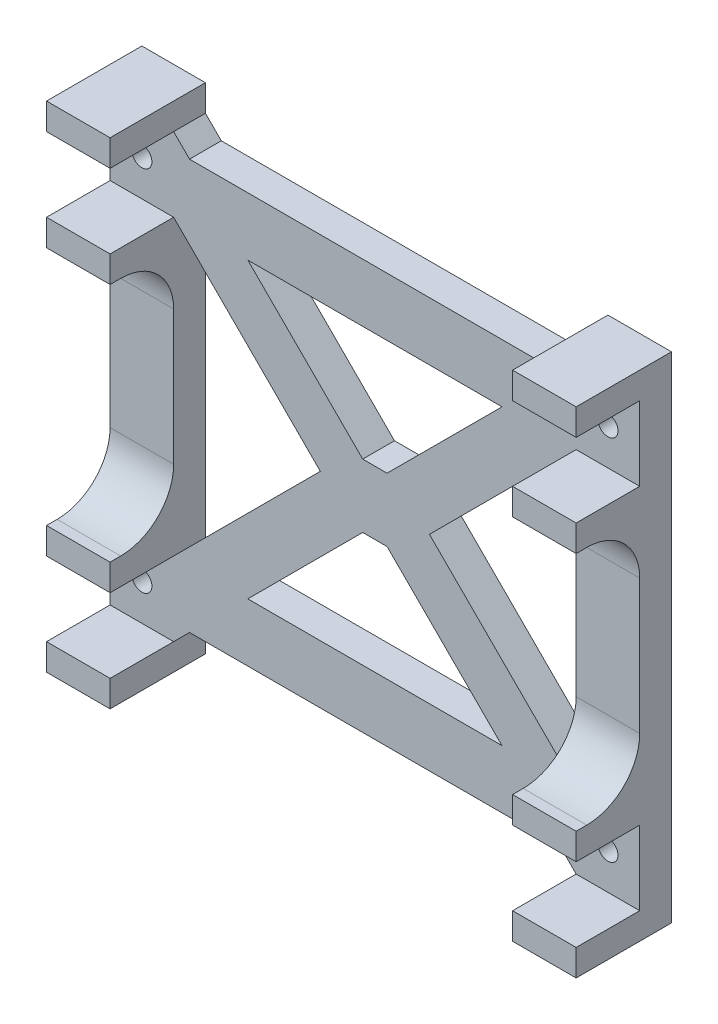
SolidWorks part; units mm, degrees
ref_plane "Plan de face" through (0, 0, 0) normal (0, 0, 1) x (1, 0, 0)
ref_plane "Plan de dessus" through (0, 0, 0) normal (0, 1, 0) x (1, 0, 0)
ref_plane "Plan de droite" through (0, 0, 0) normal (1, 0, 0) x (0, 0, -1)
sketch "Esquisse1" plane through (0, 0, 0) normal (0, 0, 1) x (1, 0, 0)
  line L1 (-3, -4) -> (3, -4)
  line L2 (-3, -4) -> (-3, 38.7)
  line L3 (-3, 38.7) -> (3, 38.7)
  line L4 (3, -4) -> (3, 38.7)
  circle A0 centre (0, 0) radius 0.95
  circle A1 centre (0, 34.7) radius 0.95
  dimension "D5" = 1.9
  dimension "D6" = 1.9
  dimension "D1" = 6
  dimension "D2" = 42.7
  dimension "D3" = 3
  dimension "D4" = 4
  dimension "D7" = 4
extrude "Boss.-Extru.1" add sketch "Esquisse1" along normal blind 3
sketch "Esquisse2" plane through (0, 0, 3) normal (0, 0, 1) x (1, 0, 0)
  line L0 (-0.95, 34.7) -> (0.95, 34.7) construction
  line L1 (3, 3.5) -> (3, 6)
  line L2 (-3, 38.2) -> (3, 38.2)
  line L3 (-3, 38.2) -> (-3, 40.7)
  line L4 (-3, 40.7) -> (3, 40.7)
  line L5 (-3, 38.7) -> (-3, -4) construction
  line L6 (-3, 31.2) -> (3, 31.2)
  line L7 (-3, 31.2) -> (-3, 28.7)
  line L8 (-3, 28.7) -> (3, 28.7)
  line L9 (3, 31.2) -> (3, 28.7)
  line L10 (3, -4) -> (3, 38.7) construction
  line L11 (-3, 17.35) -> (3, 17.35) construction
  line L12 (-3, 6) -> (3, 6)
  line L13 (-3, 3.5) -> (-3, 6)
  line L14 (-3, 3.5) -> (3, 3.5)
  line L15 (3, -3.5) -> (3, -6)
  line L16 (-3, -6) -> (3, -6)
  line L17 (-3, -3.5) -> (-3, -6)
  line L18 (-3, -3.5) -> (3, -3.5)
  line L20 (3, 38.2) -> (3, 40.7)
  circle A0 centre (0, 34.7) radius 0.95 construction
  dimension "D1" = 3.5
  dimension "D2" = 2.5
  dimension "D3" = 3.5
  dimension "D4" = 2.5
extrude "Boss.-Extru.2" add sketch "Esquisse2" along normal blind 6 and the other way up to surface other way up to face at (0.95, 0, 0)
sketch "Esquisse3" plane through (-3, 0, 0) normal (-1, 0, 0) x (0, 0, 1)
  line L0 (0, -6) -> (9, -6) construction
  line L1 (0, 40.7) -> (3, 40.7)
  line L2 (0, 40.7) -> (0, -6)
  line L3 (0, -6) -> (3, -6)
  line L4 (3, 40.7) -> (3, -6)
  line L5 (3, 28.7) -> (3, 6) construction
extrude "Boss.-Extru.4" add sketch "Esquisse3" along normal blind 44
sketch "Esquisse4" plane through (-47, 0, 0) normal (-1, 0, 0) x (0, 0, 1)
  line L0 (0, 40.7) -> (0, -6) construction
  line L1 (0, 40.7) -> (9, 40.7)
  line L2 (0, 40.7) -> (0, 38.2)
  line L3 (0, 38.2) -> (9, 38.2)
  line L4 (9, 40.7) -> (9, 38.2)
  line L5 (0, 31.2) -> (9, 31.2)
  line L6 (0, 31.2) -> (0, 28.7)
  line L7 (0, 28.7) -> (9, 28.7)
  line L8 (9, 31.2) -> (9, 28.7)
  line L10 (9, 38.2) -> (9, 40.7) construction
  line L13 (0, 17.35) -> (3, 17.35) construction
  line L14 (3, -6) -> (3, 40.7) construction
  line L15 (9, 3.5) -> (9, 6)
  line L16 (0, 6) -> (9, 6)
  line L17 (0, 3.5) -> (0, 6)
  line L18 (0, 3.5) -> (9, 3.5)
  line L19 (9, -6) -> (9, -3.5)
  line L20 (0, -3.5) -> (9, -3.5)
  line L21 (0, -6) -> (0, -3.5)
  line L22 (0, -6) -> (9, -6)
  point P11 (9, 39.45)
  dimension "D1" = 9
  dimension "D2" = 2.5
  dimension "D3" = 2.5
  dimension "D4" = 7
extrude "Boss.-Extru.5" add sketch "Esquisse4" against normal blind 6
sketch "Esquisse5" plane through (0, 0, 3) normal (0, 0, 1) x (1, 0, 0)
  line L0 (-47, -3.5) -> (-47, 3.5) construction
  line L1 (-41, -6) -> (-3, -6) construction
  line L2 (-41, 40.7) -> (-3, 40.7) construction
  line L3 (-47, 31.2) -> (-47, 38.2) construction
  circle A0 centre (-44, 34.7) radius 0.95
  circle A1 centre (-44, 0) radius 0.95
  point P12 (-47.3761, 32.9807)
  dimension "D1" = 1.9
  dimension "D4" = 1.9
  dimension "D2" = 3
  dimension "D3" = 6
  dimension "D5" = 6
  dimension "D6" = 3
extrude "Enlèv. mat.-Extru.1" cut sketch "Esquisse5" against normal up to next
sketch "Esquisse6" plane through (0, 0, 3) normal (0, 0, 1) x (1, 0, 0)
  line L0 (-34, 31.2) -> (-23.15, 20.35)
  line L1 (-41, 38.2) -> (-41, 40.7) construction
  line L2 (-10, 31.2) -> (-20.85, 20.35)
  line L3 (-3, 38.2) -> (-3, 40.7) construction
  line L4 (-34, 3.5) -> (-23.15, 14.35)
  line L5 (-20.85, 14.35) -> (-10, 3.5)
  line L6 (-41, 3.5) -> (-27.15, 17.35)
  line L7 (-3, 3.5) -> (-16.85, 17.35)
  line L8 (-41, 31.2) -> (-27.15, 17.35)
  line L9 (-3, 31.2) -> (-16.85, 17.35)
  line L10 (-3, 28.7) -> (-3, 31.2) construction
  line L11 (-41, 38.2) -> (-39.5, 36.7)
  line L12 (-41, 28.7) -> (-41, 6)
  line L13 (-3, 28.7) -> (-3, 6)
  line L14 (-10, 31.2) -> (-34, 31.2)
  line L15 (-23.15, 14.35) -> (-20.85, 14.35)
  line L16 (-41, -6) -> (-41, -3.5) construction
  line L17 (-20.85, 20.35) -> (-23.15, 20.35)
  line L18 (-34, 3.5) -> (-10, 3.5)
  line L19 (-41, -3.5) -> (-39.5, -2)
  line L20 (-39.5, -2) -> (-4.5, -2)
  line L21 (-3, -3.5) -> (-4.5, -2)
  line L23 (-41, -6) -> (-3, -6) construction
  line L24 (-3, -6) -> (-3, -3.5) construction
  line L25 (-39.5, 36.7) -> (-4.5, 36.7)
  line L26 (-3, 38.2) -> (-4.5, 36.7)
  line L27 (-41, 40.7) -> (-3, 40.7) construction
  dimension "D1" = 135
  dimension "D2" = 135
  dimension "D3" = 45
  dimension "D4" = 135
  dimension "D5" = 135
  dimension "D6" = 4
  dimension "D7" = 135
  dimension "D8" = 135
  dimension "D9" = 4
extrude "Enlèv. mat.-Extru.2" cut sketch "Esquisse6" against normal up to next
fillet "Congé1" radius 5 7 edges at (-44, 28.7, 3) (-44, 6, 3)
